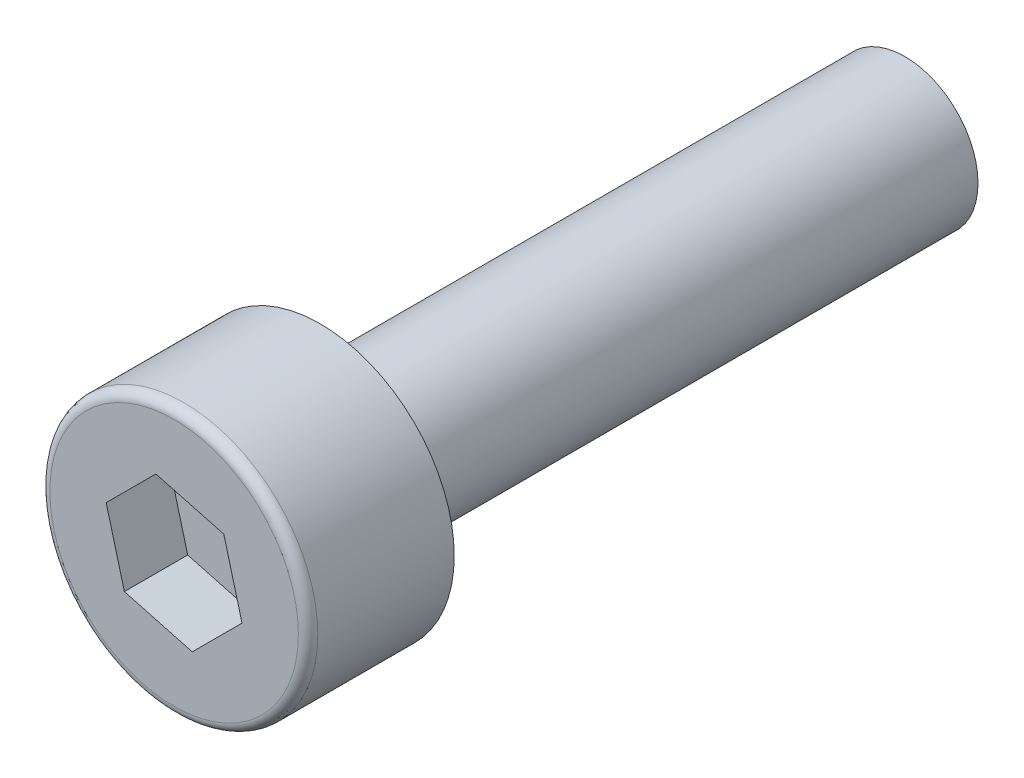
SolidWorks part; units mm, degrees
ref_plane "前视基准面" through (0, 0, 0) normal (0, 0, 1) x (1, 0, 0)
ref_plane "上视基准面" through (0, 0, 0) normal (0, 1, 0) x (1, 0, 0)
ref_plane "右视基准面" through (0, 0, 0) normal (1, 0, 0) x (0, 0, -1)
sketch "草图1" plane through (0, 0, 0) normal (0, 0, 1) x (1, 0, 0)
  circle A0 centre (0, 0) radius 2.75
  dimension "D1" = 5.5
extrude "凸台-拉伸1" add sketch "草图1" along normal blind 3
sketch "草图2" plane through (0, 0, 3) normal (0, 0, 1) x (1, 0, 0)
  line L1 (-1.0206, -1.0206) -> (0.3736, -1.3942)
  line L2 (0.3736, -1.3942) -> (1.3942, -0.3736)
  line L3 (1.3942, -0.3736) -> (1.0206, 1.0206)
  line L4 (1.0206, 1.0206) -> (-0.3736, 1.3942)
  line L5 (-0.3736, 1.3942) -> (-1.3942, 0.3736)
  line L6 (-1.3942, 0.3736) -> (-1.0206, -1.0206)
  circle A0 centre (0, 0) radius 1.25 construction
  dimension "D1" = 2.5
extrude "切除-拉伸1" cut sketch "草图2" against normal blind 1.3
sketch "草图3" plane through (0, 0, 0) normal (0, 0, -1) x (-1, 0, 0)
  circle A0 centre (0, 0) radius 1.5
  dimension "D1" = 3
extrude "凸台-拉伸2" add sketch "草图3" along normal blind 12
fillet "圆角1" radius 0.2 1 edges at (2.75, 0, 3)
